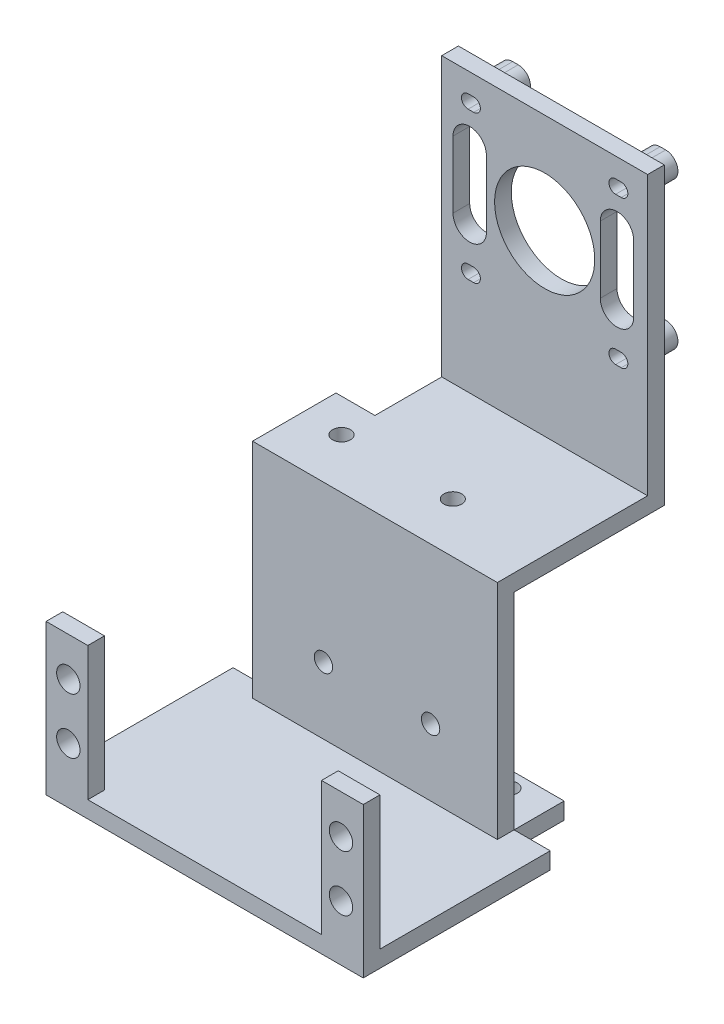
SolidWorks part; units mm, degrees
ref_plane "前视基准面" through (0, 0, 0) normal (0, 0, 1) x (1, 0, 0)
ref_plane "上视基准面" through (0, 0, 0) normal (0, 1, 0) x (1, 0, 0)
ref_plane "右视基准面" through (0, 0, 0) normal (1, 0, 0) x (0, 0, -1)
sketch "草图1" plane through (0, 0, 0) normal (0, 1, 0) x (1, 0, 0)
  line L1 (-28.5, 25.5) -> (28.5, 25.5)
  line L2 (-28.5, 25.5) -> (-28.5, -25.5)
  line L3 (-28.5, -25.5) -> (28.5, -25.5)
  line L4 (28.5, 25.5) -> (28.5, -25.5)
  line L5 (-28.5, 25.5) -> (28.5, -25.5) construction
  line L6 (-28.5, -25.5) -> (28.5, 25.5) construction
  point P0 (0, 0)
  dimension "D1" = 57
  dimension "D2" = 51
extrude "凸台-拉伸1" add sketch "草图1" along normal blind 3
ref_plane "基准面1" through (0, 3, 0) normal (0, 1, 0) x (1, 0, 0)
sketch "草图3" plane through (0, 3, 0) normal (0, 1, 0) x (1, 0, 0)
  line L0 (28.5, 25.5) -> (-28.5, 25.5) construction
  line L1 (-22, 25.5) -> (22, 25.5)
  line L2 (-22, 25.5) -> (-22, 22.5)
  line L3 (-22, 22.5) -> (22, 22.5)
  line L4 (22, 25.5) -> (22, 22.5)
  line L5 (-28.5, 25.5) -> (-28.5, -25.5) construction
  dimension "D1" = 44
  dimension "D2" = 6.5
  dimension "D3" = 3
extrude "凸台-拉伸3" add sketch "草图3" along normal blind 24
sketch "草图5" plane through (0, 3, 0) normal (0, 1, 0) x (1, 0, 0)
  line L0 (28.5, -25.5) -> (28.5, 25.5) construction
  line L1 (-28.5, -5.1) -> (28.5, -5.1)
  line L2 (-28.5, -5.1) -> (-28.5, -8.1)
  line L3 (-28.5, -8.1) -> (28.5, -8.1)
  line L4 (28.5, -5.1) -> (28.5, -8.1)
  line L5 (-28.5, -5.1) -> (28.5, -8.1) construction
  line L6 (-28.5, -8.1) -> (28.5, -5.1) construction
  line L8 (28.5, 25.5) -> (22, 25.5) construction
  line L9 (-28.5, 25.5) -> (-28.5, -25.5) construction
  point P0 (0, -6.6)
  dimension "D1" = 3
  dimension "D2" = 33.6
extrude "凸台-拉伸4" add sketch "草图5" along normal blind 24
ref_plane "基准面3" through (0, 0, 5.1) normal (0, 0, -1) x (-1, 0, 0)
sketch "草图7" plane through (0, 0, 5.1) normal (0, 0, -1) x (-1, 0, 0)
  line L0 (-28.5, 15) -> (28.5, 15) construction
  line L1 (-24.5, 20) -> (24.5, 20) construction
  line L2 (-24.5, 20) -> (-24.5, 10) construction
  line L3 (-24.5, 10) -> (24.5, 10) construction
  line L4 (24.5, 20) -> (24.5, 10) construction
  line L5 (-24.5, 20) -> (24.5, 10) construction
  line L6 (-24.5, 10) -> (24.5, 20) construction
  line L7 (-28.5, 27) -> (-28.5, 3) construction
  line L8 (28.5, 27) -> (28.5, 3) construction
  circle A0 centre (-24.5, 20) radius 2.1
  circle A1 centre (-24.5, 10) radius 2.1
  circle A2 centre (24.5, 20) radius 2.1
  circle A3 centre (24.5, 10) radius 2.1
  point P0 (0, 15)
  dimension "D3" = 4.2
  dimension "D4" = 4.2
  dimension "D5" = 4.2
  dimension "D6" = 4.2
  dimension "D1" = 49
  dimension "D2" = 10
extrude "切除-拉伸1" cut sketch "草图7" against normal blind 3
sketch "草图8" plane through (0, 0, 5.1) normal (0, 0, -1) x (-1, 0, 0)
  line L0 (-22, 27) -> (22, 27) construction
  line L1 (21, 3) -> (-21, 3)
  line L2 (21, 3) -> (21, 27)
  line L3 (21, 27) -> (-21, 27)
  line L4 (-21, 3) -> (-21, 27)
  line L5 (21, 3) -> (-21, 27) construction
  line L6 (21, 27) -> (-21, 3) construction
  point P0 (0, 15)
  dimension "D1" = 42
  dimension "D2" = 24
extrude "切除-拉伸2" cut sketch "草图8" against normal blind 3
ref_plane "基准面4" through (0, 27, 0) normal (0, 1, 0) x (1, 0, 0)
sketch "草图10" plane through (0, 27, 0) normal (0, 1, 0) x (1, 0, 0)
  line L1 (-22, 22.5) -> (22, 22.5)
  line L2 (-22, 22.5) -> (-22, 25.5)
  line L3 (-22, 25.5) -> (22, 25.5)
  line L4 (22, 22.5) -> (22, 25.5)
extrude "凸台-拉伸5" add sketch "草图10" along normal blind 55
ref_plane "基准面5" through (0, 0, -25.5) normal (0, 0, -1) x (-1, 0, 0)
sketch "草图11" plane through (0, 0, -25.5) normal (0, 0, -1) x (-1, 0, 0)
  line L0 (-22, 82) -> (22, 82) construction
  line L1 (-13.2, 85) -> (13.2, 85) construction
  line L2 (-13.2, 85) -> (-13.2, 58.6) construction
  line L3 (-13.2, 58.6) -> (13.2, 58.6) construction
  line L4 (13.2, 85) -> (13.2, 58.6) construction
  line L5 (-13.2, 85) -> (13.2, 58.6) construction
  line L6 (-13.2, 58.6) -> (13.2, 85) construction
  circle A0 centre (-13.2, 85) radius 2.25
  circle A1 centre (13.2, 85) radius 2.25
  circle A2 centre (-13.2, 58.6) radius 2.25
  circle A3 centre (13.2, 58.6) radius 2.25
  point P0 (0, 71.8)
  dimension "D3" = 4.5
  dimension "D4" = 4.5
  dimension "D5" = 4.5
  dimension "D6" = 4.5
  dimension "D1" = 26.4
  dimension "D2" = 26.4
  dimension "D7" = 3
extrude "凸台-拉伸6" add sketch "草图11" against normal blind 8
ref_plane "基准面6" through (0, 0, -22.5) normal (0, 0, 1) x (1, 0, 0)
sketch "草图12" plane through (0, 0, -22.5) normal (0, 0, 1) x (1, 0, 0)
  line L0 (-13.2, 58.6) -> (13.2, 58.6) construction
  line L1 (-10.2, 62.6) -> (2.8, 62.6)
  line L2 (-10.2, 62.6) -> (-10.2, 54.6)
  line L3 (-10.2, 54.6) -> (2.8, 54.6)
  line L4 (2.8, 62.6) -> (2.8, 54.6)
  line L5 (-10.2, 62.6) -> (2.8, 54.6) construction
  line L6 (-10.2, 54.6) -> (2.8, 62.6) construction
  point P0 (-3.7, 58.6)
  dimension "D1" = 8
  dimension "D2" = 13
  dimension "D3" = 3
extrude "切除-拉伸4" cut sketch "草图12" against normal blind 8
ref_plane "基准面7" through (0, 0, -17.5) normal (0, 0, 1) x (1, 0, 0)
sketch "草图13" plane through (0, 0, -17.5) normal (0, 0, 1) x (1, 0, 0)
  circle A0 centre (13.2, 85) radius 1.1
  circle A1 centre (-13.2, 85) radius 1.1
  circle A2 centre (-13.2, 58.6) radius 1.1
  circle A3 centre (13.2, 58.6) radius 1.1
  dimension "D1" = 2.2
  dimension "D2" = 2.2
  dimension "D3" = 2.2
  dimension "D4" = 2.2
extrude "切除-拉伸5" cut sketch "草图13" against normal blind 5
sketch "草图14" plane through (0, 0, -25.5) normal (0, 0, -1) x (-1, 0, 0)
  line L0 (-28.5, 0) -> (28.5, 0) construction
  line L1 (-22, 0) -> (22, 0)
  line L2 (-22, 0) -> (-22, 3)
  line L3 (-22, 3) -> (22, 3)
  line L4 (22, 0) -> (22, 3)
  line L5 (28.05, 3) -> (-28.05, 3) construction
  line L6 (21, 3) -> (28.5, 3) construction
  line L7 (-28.5, 3) -> (-28.5, 0) construction
  dimension "D1" = 44
  dimension "D2" = 6.5
extrude "凸台-拉伸7" add sketch "草图14" along normal blind 6
sketch "草图15" plane through (0, 0, -25.5) normal (0, 0, -1) x (-1, 0, 0)
  line L0 (-22, 82) -> (-22, 3) construction
  line L1 (-22, 43) -> (22, 43)
  line L2 (-22, 43) -> (-22, 40)
  line L3 (-22, 40) -> (22, 40)
  line L4 (22, 43) -> (22, 40)
  line L5 (22, 82) -> (22, 3) construction
  line L7 (-22, 0) -> (22, 0) construction
  dimension "D1" = 40
  dimension "D2" = 3
extrude "凸台-拉伸8" add sketch "草图15" along normal blind 9
ref_plane "基准面8" through (0, 40, 0) normal (0, -1, 0) x (-1, 0, 0)
sketch "草图16" plane through (0, 40, 0) normal (0, -1, 0) x (-1, 0, 0)
  line L0 (22, 31.5) -> (22, 25.5) construction
  line L1 (-22, 31.5) -> (22, 31.5) construction
  circle A0 centre (15, 31.5) radius 1.6
  circle A1 centre (-5, 31.5) radius 1.6
  dimension "D1" = 7
  dimension "D2" = 20
  dimension "D3" = 3.2
  dimension "D4" = 3.2
  dimension "D5" = 0
  dimension "D6" = 0
extrude "切除-拉伸6" cut sketch "草图16" against normal blind 9
sketch "草图17" plane through (0, 0, 0) normal (0, 1, 0) x (1, 0, 0)
  line L0 (-22, 34.5) -> (-22, 25.5) construction
  line L1 (-22, 34.5) -> (22, 34.5) construction
  circle A0 centre (-5, 31.5) radius 1.6
  circle A1 centre (15, 31.5) radius 1.6
  dimension "D1" = 17
  dimension "D2" = 20
  dimension "D3" = 3
  dimension "D4" = 3.2
  dimension "3.2" = 3.2
  dimension "D5" = 3
extrude "切除-拉伸8" cut sketch "草图17" along normal blind 9
sketch "草图18" plane through (0, 3, 0) normal (0, 1, 0) x (1, 0, 0)
  line L1 (-28.5, -25.5) -> (28.5, -25.5)
  line L2 (-28.5, -25.5) -> (-28.5, -43.1)
  line L3 (-28.5, -43.1) -> (28.5, -43.1)
  line L4 (28.5, -25.5) -> (28.5, -43.1)
  dimension "D1" = 17.6
extrude "凸台-拉伸9" add sketch "草图18" against normal blind 3
sketch "草图19" plane through (0, 3, 0) normal (0, 1, 0) x (1, 0, 0)
  line L1 (-28.5, -43.1) -> (28.5, -43.1)
  line L2 (-28.5, -43.1) -> (-28.5, -40.1)
  line L3 (-28.5, -40.1) -> (28.5, -40.1)
  line L4 (28.5, -43.1) -> (28.5, -40.1)
  line L5 (28.5, -43.1) -> (28.5, -8.1) construction
  dimension "D1" = 3
  dimension "D2" = 57
extrude "凸台-拉伸10" add sketch "草图19" along normal blind 25
sketch "草图20" plane through (0, 0, -25.5) normal (0, 0, -1) x (-1, 0, 0)
  line L1 (-29.895, 90.1394) -> (22, 90.1394)
  line L2 (-29.895, 90.1394) -> (-29.895, 43)
  line L3 (-29.895, 43) -> (22, 43)
  line L4 (22, 90.1394) -> (22, 43)
extrude "切除-拉伸9" cut sketch "草图20" against normal blind 10
sketch "草图21" plane through (-28.5, 0, 0) normal (-1, 0, 0) x (0, 0, 1)
  line L9 (43.1, 0) -> (40.1, 0)
  line L10 (43.1, 0) -> (43.1, 32)
  line L11 (43.1, 32) -> (40.1, 32)
  line L12 (40.1, 0) -> (40.1, 32)
  dimension "D1" = 32
  dimension "D2" = 3
extrude "凸台-拉伸11" add sketch "草图21" along normal blind 34
sketch "草图22" plane through (0, 0, 40.1) normal (0, 0, -1) x (-1, 0, 0)
  line L0 (62.5, 32) -> (62.5, 0) construction
  line L1 (33.25, 2.75) -> (59.75, 2.75) construction
  line L2 (33.25, 2.75) -> (33.25, 29.25) construction
  line L3 (33.25, 29.25) -> (59.75, 29.25) construction
  line L4 (59.75, 2.75) -> (59.75, 29.25) construction
  line L5 (33.25, 2.75) -> (59.75, 29.25) construction
  line L6 (33.25, 29.25) -> (59.75, 2.75) construction
  circle A0 centre (59.75, 29.25) radius 1.2
  circle A1 centre (59.75, 2.75) radius 1.2
  circle A2 centre (33.25, 2.75) radius 1.2
  circle A3 centre (33.25, 29.25) radius 1.2
  circle A5 centre (59.75, 2.75) radius 2.25
  circle A6 centre (59.75, 29.25) radius 2.25
  circle A7 centre (33.25, 29.25) radius 2.25
  circle A8 centre (33.25, 2.75) radius 2.25
  point P0 (46.5, 16)
  dimension "D2" = 2.4
  dimension "D3" = 2.4
  dimension "D4" = 2.4
  dimension "D5" = 2.4
  dimension "D6" = 4.5
  dimension "D8" = 4.5
  dimension "D9" = 4.5
  dimension "D10" = 4.5
  dimension "D1" = 26.5
  dimension "D7" = 16
extrude "凸台-拉伸12" add sketch "草图22" along normal blind 5
sketch "草图24" plane through (0, 0, 40.1) normal (0, 0, -1) x (-1, 0, 0)
  line L1 (33.25, 29.25) -> (59.75, 29.25) construction
  line L2 (33.25, 29.25) -> (33.25, 2.75) construction
  line L3 (33.25, 2.75) -> (59.75, 2.75) construction
  line L4 (59.75, 29.25) -> (59.75, 2.75) construction
  circle A0 centre (46.5, 16) radius 9
  dimension "D1" = 18
extrude "切除-拉伸11" cut sketch "草图24" against normal blind 5
sketch "草图25" plane through (0, 0, 43.1) normal (0, 0, 1) x (1, 0, 0)
  line L0 (-28.5, 28) -> (-28.5, 32) construction
  line L1 (-62.5, 0) -> (28.5, 0) construction
  circle A0 centre (-9.25, 15) radius 1.65
  circle A1 centre (10, 15) radius 1.65
  dimension "D1" = 3.3
  dimension "D3" = 3.3
  dimension "D4" = 19.25
  dimension "D5" = 15
  dimension "D2" = 19.25
extrude "切除-拉伸12" cut sketch "草图25" against normal blind 10
sketch "草图26" plane through (0, 0, 40.1) normal (0, 0, -1) x (-1, 0, 0)
  circle A1 centre (33.25, 2.75) radius 1.1
  circle A2 centre (33.25, 29.25) radius 1.2 construction
  circle A3 centre (33.25, 29.25) radius 1.2
  circle A4 centre (59.75, 29.25) radius 1.2 construction
  circle A5 centre (59.75, 29.25) radius 1.2
  circle A6 centre (59.75, 2.75) radius 1.2 construction
  circle A7 centre (59.75, 2.75) radius 1.2
  dimension "D1" = 2.2
extrude "切除-拉伸13" cut sketch "草图26" against normal blind 10
sketch "草图27" plane through (0, 0, 43.1) normal (0, 0, 1) x (1, 0, 0)
  line L0 (-31.25, 9.5) -> (-31.25, 22.5) construction
  line L1 (-46.5, 16) -> (-31.25, 16) construction
  line L2 (-34.75, 9.5) -> (-34.75, 22.5)
  line L3 (-27.75, 9.5) -> (-27.75, 22.5)
  line L5 (-79.3787, 5.5) -> (-58.8487, 5.5)
  line L6 (-79.3787, 5.5) -> (-79.3787, 26.5)
  line L7 (-79.3787, 26.5) -> (-58.8487, 26.5)
  line L8 (-58.8487, 5.5) -> (-58.8487, 26.5)
  line L9 (-79.3787, 5.5) -> (-58.8487, 26.5) construction
  line L10 (-79.3787, 26.5) -> (-58.8487, 5.5) construction
  arc A0 (-34.75, 9.5) -> (-27.75, 9.5) centre (-31.25, 9.5) ccw
  arc A1 (-27.75, 22.5) -> (-34.75, 22.5) centre (-31.25, 22.5) ccw
  circle A2 centre (-33.25, 2.75) radius 1.2 construction
  point P4 (-31.25, 16)
  point P13 (-69.1137, 16)
  dimension "D1" = 3.5
  dimension "D2" = 13
  dimension "D3" = 2
  dimension "D4" = 21
  dimension "D5" = 20.53
extrude "切除-拉伸14" cut sketch "草图27" against normal blind 10
sketch "草图28" plane through (0, 0, 0) normal (0, -1, 0) x (1, 0, 0)
  line L0 (22, -34.5) -> (22, -25.5) construction
  line L1 (-22, -31.5) -> (22, -31.5)
  line L2 (-22, -31.5) -> (-22, -34.5)
  line L3 (-22, -34.5) -> (22, -34.5)
  line L4 (22, -31.5) -> (22, -34.5)
  dimension "D1" = 3
extrude "凸台-拉伸13" add sketch "草图28" against normal blind 3
sketch "草图29" plane through (0, 43, 0) normal (0, 1, 0) x (1, 0, 0)
  line L0 (22, 34.5) -> (22, 22.5) construction
  line L1 (-22, 34.5) -> (22, 34.5)
  line L2 (-22, 34.5) -> (-22, 37.5)
  line L3 (-22, 37.5) -> (22, 37.5)
  line L4 (22, 34.5) -> (22, 37.5)
  dimension "D1" = 3
extrude "凸台-拉伸14" add sketch "草图29" against normal blind 3
sketch "草图30" plane through (0, 0, 0) normal (0, -1, 0) x (1, 0, 0)
  line L0 (16.6, -31.5) -> (13.4, -31.5) construction
  circle A0 centre (15, -31.5) radius 1.6
  circle A1 centre (-5, -31.5) radius 1.6
extrude "切除-拉伸15" cut sketch "草图30" against normal blind 3
sketch "草图32" plane through (0, 3, 0) normal (0, 1, 0) x (1, 0, 0)
  line L1 (28.5, -8.1) -> (-66.4302, -8.1)
  line L2 (28.5, -8.1) -> (28.5, -49.0165)
  line L3 (28.5, -49.0165) -> (-66.4302, -49.0165)
  line L4 (-66.4302, -8.1) -> (-66.4302, -49.0165)
sketch "草图33" plane through (0, 0, -22.5) normal (0, 0, 1) x (1, 0, 0)
  circle A0 centre (-9.25, 15) radius 1.65
  circle A1 centre (10, 15) radius 1.65
extrude "切除-拉伸16" cut sketch "草图33" against normal blind 3
sketch "草图34" plane through (-22, 0, 0) normal (-1, 0, 0) x (0, 0, 1)
  line L0 (-25.5, 31.35) -> (-25.5, -31.35) construction
  line L1 (-25.5, 3) -> (-22.5, 3)
  line L2 (-25.5, 3) -> (-25.5, 40)
  line L3 (-25.5, 40) -> (-22.5, 40)
  line L4 (-22.5, 3) -> (-22.5, 40)
  line L5 (28.05, 3) -> (-28.05, 3) construction
  line L6 (-22.5, -24.2) -> (-22.5, 24.2) construction
  line L7 (-4.95, 40) -> (4.95, 40) construction
extrude "切除-拉伸21" cut sketch "草图32" against normal through all both and the other way through all
sketch "草图40" plane through (0, 0, -37.5) normal (0, 0, -1) x (-1, 0, 0)
  line L1 (-22, 43) -> (15, 43)
  line L2 (-22, 43) -> (-22, 40)
  line L3 (-22, 40) -> (15, 40)
  line L4 (15, 43) -> (15, 40)
  line L7 (-22, 43) -> (22, 43) construction
  line L8 (-22, 40) -> (-22, 43) construction
  line L9 (-4.95, 40) -> (4.95, 40) construction
  dimension "D1" = 3
  dimension "D2" = 37
extrude "凸台-拉伸19" add sketch "草图40" along normal blind 15
sketch "草图41" plane through (0, 43, 0) normal (0, 1, 0) x (1, 0, 0)
  line L1 (-15, 52.5) -> (22, 52.5)
  line L2 (-15, 52.5) -> (-15, 49.5)
  line L3 (-15, 49.5) -> (22, 49.5)
  line L4 (22, 52.5) -> (22, 49.5)
  dimension "D1" = 3
  dimension "D2" = 37
extrude "凸台-拉伸20" add sketch "草图41" along normal blind 50
sketch "草图42" plane through (0, 0, -52.5) normal (0, 0, -1) x (-1, 0, 0)
  line L0 (-22, 93) -> (15, 93) construction
  line L1 (-16.75, 61.75) -> (9.75, 61.75) construction
  line L2 (-16.75, 61.75) -> (-16.75, 88.25) construction
  line L3 (-16.75, 88.25) -> (9.75, 88.25) construction
  line L4 (9.75, 61.75) -> (9.75, 88.25) construction
  line L5 (-16.75, 61.75) -> (9.75, 88.25) construction
  line L6 (-16.75, 88.25) -> (9.75, 61.75) construction
  line L7 (-3.5, 93) -> (-3.5, 75) construction
  line L8 (-17.25, 88.25) -> (-16.25, 88.25) construction
  line L9 (10.25, 61.75) -> (9.25, 61.75) construction
  line L10 (-17.25, 89.45) -> (-16.25, 89.45)
  line L11 (-17.25, 87.05) -> (-16.25, 87.05)
  line L13 (10.25, 60.55) -> (9.25, 60.55)
  line L14 (10.25, 62.95) -> (9.25, 62.95)
  line L15 (-16.25, 61.75) -> (-17.25, 61.75) construction
  line L16 (-16.25, 60.55) -> (-17.25, 60.55)
  line L17 (-16.25, 62.95) -> (-17.25, 62.95)
  line L18 (10.25, 88.25) -> (9.25, 88.25) construction
  line L19 (10.25, 87.05) -> (9.25, 87.05)
  line L20 (10.25, 89.45) -> (9.25, 89.45)
  arc A0 (-17.25, 89.45) -> (-17.25, 87.05) centre (-17.25, 88.25) ccw
  arc A1 (-16.25, 87.05) -> (-16.25, 89.45) centre (-16.25, 88.25) ccw
  arc A2 (10.25, 60.55) -> (10.25, 62.95) centre (10.25, 61.75) ccw
  arc A3 (9.25, 62.95) -> (9.25, 60.55) centre (9.25, 61.75) ccw
  arc A4 (-16.25, 60.55) -> (-16.25, 62.95) centre (-16.25, 61.75) ccw
  arc A5 (-17.25, 62.95) -> (-17.25, 60.55) centre (-17.25, 61.75) ccw
  arc A6 (10.25, 87.05) -> (10.25, 89.45) centre (10.25, 88.25) ccw
  arc A7 (9.25, 89.45) -> (9.25, 87.05) centre (9.25, 88.25) ccw
  circle A8 centre (-3.5, 75) radius 9
  point P0 (-3.5, 75)
  point P13 (-16.75, 88.25)
  point P20 (9.75, 61.75)
  point P26 (-16.75, 61.75)
  point P33 (9.75, 88.25)
  dimension "D4" = 1.2
  dimension "D6" = 1.2
  dimension "D8" = 1.2
  dimension "D10" = 1.2
  dimension "D11" = 18
  dimension "D1" = 26.5
  dimension "D2" = 18
  dimension "D3" = 1
  dimension "D5" = 1
  dimension "D7" = 1
  dimension "D9" = 1
extrude "切除-拉伸22" cut sketch "草图42" against normal blind 45
sketch "草图43" plane through (0, 0, -52.5) normal (0, 0, -1) x (-1, 0, 0)
  line L0 (-17.25, 60.55) -> (-16.25, 60.55) construction
  line L1 (-16.25, 62.95) -> (-17.25, 62.95) construction
  line L2 (9.25, 60.55) -> (10.25, 60.55) construction
  line L3 (10.25, 62.95) -> (9.25, 62.95) construction
  line L4 (9.25, 87.05) -> (10.25, 87.05) construction
  line L5 (10.25, 89.45) -> (9.25, 89.45) construction
  line L6 (-17.25, 87.05) -> (-16.25, 87.05) construction
  line L7 (-16.25, 89.45) -> (-17.25, 89.45) construction
  line L8 (-17.25, 60.55) -> (-16.25, 60.55)
  line L9 (-16.25, 62.95) -> (-17.25, 62.95)
  line L10 (9.25, 60.55) -> (10.25, 60.55)
  line L11 (10.25, 62.95) -> (9.25, 62.95)
  line L12 (9.25, 87.05) -> (10.25, 87.05)
  line L13 (10.25, 89.45) -> (9.25, 89.45)
  line L14 (-17.25, 87.05) -> (-16.25, 87.05)
  line L15 (-16.25, 89.45) -> (-17.25, 89.45)
  line L16 (-17.25, 59.55) -> (-16.25, 59.55)
  line L17 (-16.25, 63.95) -> (-17.25, 63.95)
  line L18 (9.25, 59.55) -> (10.25, 59.55)
  line L19 (10.25, 63.95) -> (9.25, 63.95)
  line L20 (9.25, 86.05) -> (10.25, 86.05)
  line L21 (10.25, 90.45) -> (9.25, 90.45)
  line L22 (-17.25, 86.05) -> (-16.25, 86.05)
  line L23 (-16.25, 90.45) -> (-17.25, 90.45)
  arc A0 (-17.25, 62.95) -> (-17.25, 60.55) centre (-17.25, 61.75) ccw construction
  arc A1 (-16.25, 60.55) -> (-16.25, 62.95) centre (-16.25, 61.75) ccw construction
  arc A2 (9.25, 62.95) -> (9.25, 60.55) centre (9.25, 61.75) ccw construction
  arc A3 (10.25, 60.55) -> (10.25, 62.95) centre (10.25, 61.75) ccw construction
  arc A4 (10.25, 87.05) -> (10.25, 89.45) centre (10.25, 88.25) ccw construction
  arc A5 (9.25, 89.45) -> (9.25, 87.05) centre (9.25, 88.25) ccw construction
  arc A6 (-16.25, 87.05) -> (-16.25, 89.45) centre (-16.25, 88.25) ccw construction
  arc A7 (-17.25, 89.45) -> (-17.25, 87.05) centre (-17.25, 88.25) ccw construction
  arc A8 (-17.25, 62.95) -> (-17.25, 60.55) centre (-17.25, 61.75) ccw
  arc A9 (-16.25, 60.55) -> (-16.25, 62.95) centre (-16.25, 61.75) ccw
  arc A10 (9.25, 62.95) -> (9.25, 60.55) centre (9.25, 61.75) ccw
  arc A11 (10.25, 60.55) -> (10.25, 62.95) centre (10.25, 61.75) ccw
  arc A12 (10.25, 87.05) -> (10.25, 89.45) centre (10.25, 88.25) ccw
  arc A13 (9.25, 89.45) -> (9.25, 87.05) centre (9.25, 88.25) ccw
  arc A14 (-16.25, 87.05) -> (-16.25, 89.45) centre (-16.25, 88.25) ccw
  arc A15 (-17.25, 89.45) -> (-17.25, 87.05) centre (-17.25, 88.25) ccw
  arc A16 (-16.25, 59.55) -> (-16.25, 63.95) centre (-16.25, 61.75) ccw
  arc A17 (-17.25, 63.95) -> (-17.25, 59.55) centre (-17.25, 61.75) ccw
  arc A18 (10.25, 59.55) -> (10.25, 63.95) centre (10.25, 61.75) ccw
  arc A19 (9.25, 63.95) -> (9.25, 59.55) centre (9.25, 61.75) ccw
  arc A20 (10.25, 86.05) -> (10.25, 90.45) centre (10.25, 88.25) ccw
  arc A21 (9.25, 90.45) -> (9.25, 86.05) centre (9.25, 88.25) ccw
  arc A22 (-16.25, 86.05) -> (-16.25, 90.45) centre (-16.25, 88.25) ccw
  arc A23 (-17.25, 90.45) -> (-17.25, 86.05) centre (-17.25, 88.25) ccw
  dimension "D1" = 1
extrude "凸台-拉伸21" add sketch "草图43" along normal blind 5
ref_plane "基准面9" through (0, 0, -52.5) normal (0, 0, -1) x (-1, 0, 0)
sketch "草图44" plane through (0, 0, -52.5) normal (0, 0, -1) x (-1, 0, 0)
  line L0 (-16.5, 81.5) -> (-16.5, 69.5) construction
  line L1 (-13.5, 81.5) -> (-13.5, 69.5)
  line L2 (-19.5, 81.5) -> (-19.5, 69.5)
  line L3 (-3.2647, 83.9969) -> (-3.2647, 66.0031) construction
  line L4 (-22, 93) -> (-22, 40) construction
  line L5 (-22, 93) -> (15, 93) construction
  line L6 (9.9706, 81.5) -> (9.9706, 69.5) construction
  line L7 (6.9706, 81.5) -> (6.9706, 69.5)
  line L8 (12.9706, 81.5) -> (12.9706, 69.5)
  arc A0 (-13.5, 81.5) -> (-19.5, 81.5) centre (-16.5, 81.5) ccw
  arc A1 (-19.5, 69.5) -> (-13.5, 69.5) centre (-16.5, 69.5) ccw
  circle A2 centre (-3.5, 75) radius 9 construction
  arc A3 (6.9706, 81.5) -> (12.9706, 81.5) centre (9.9706, 81.5) cw
  arc A4 (12.9706, 69.5) -> (6.9706, 69.5) centre (9.9706, 69.5) cw
  point P2 (-16.5, 75.5)
  point P17 (9.9706, 75.5)
  dimension "D1" = 3
  dimension "D4" = 11.5
  dimension "D2" = 12
  dimension "D3" = 2.5
extrude "切除-拉伸23" cut sketch "草图44" against normal blind 10
